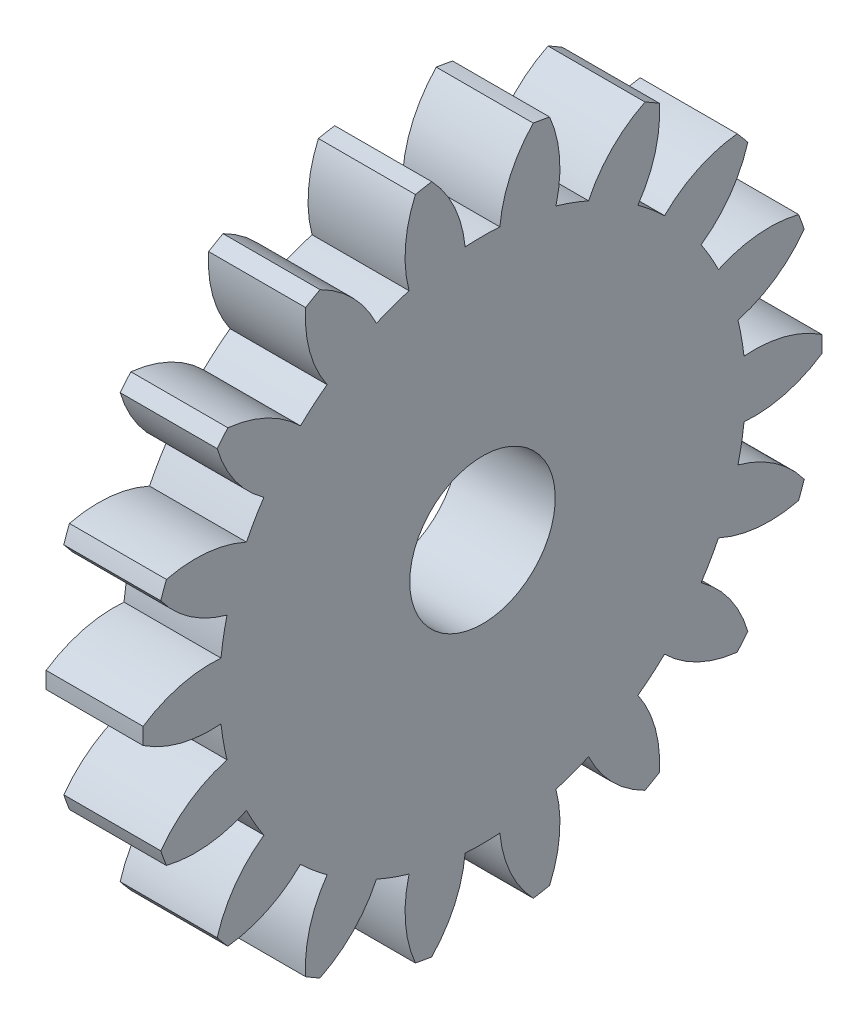
SolidWorks part; units mm, degrees
material "AISI 347 Annealed Stainless Steel (SS)"
ref_plane "Plane1" through (0, 0, 0) normal (0, 0, 1) x (1, 0, 0)
ref_plane "Plane2" through (0, 0, 0) normal (0, 1, 0) x (1, 0, 0)
ref_plane "Plane3" through (0, 0, 0) normal (1, 0, 0) x (0, 0, -1)
sketch "HoldingSke" plane through (0, 0, 0) normal (0, 1, 0) x (1, 0, 0)
  line L0 (0, 0) -> (1.3587, -0.4415)
  line L1 (-15, 0) -> (100, 0) construction
  line L2 (0, 0) -> (-2.1039, 2.3779)
  line L3 (0, 0) -> (-11.863, 4.5341)
  line L4 (0, 0) -> (8.2133, 2.6687)
  line L5 (0, 0) -> (-46.8476, -17.4728)
  line L6 (0, 0) -> (-1.6579, -1.1186)
  line L7 (-2.1039, 2.3779) -> (8.6586, 51.2059)
  line L8 (-76.2, 54.61) -> (-75.7, 54.61)
  line L9 (-71.009, 38.7566) -> (-53.1078, 45.2721)
  line L10 (-76.2, 71.12) -> (104.1128, 71.12)
  line L11 (0, 0) -> (-2, 0)
  line L12 (-76.2, 101.6) -> (-76.173, 101.6)
  line L13 (24.9733, 27.94) -> (52.9518, 28.4284)
  line L14 (24.9733, 27.94) -> (24.9743, 27.94)
  line L15 (24.9733, 27.94) -> (100.4006, 29.5858)
  line L16 (-63.627, -0.7) -> (-12.827, -0.7)
  circle A0 centre (0, 0) radius 1.5
  circle A1 centre (0, 0) radius 5.424
  circle A2 centre (0, 0) radius 37.5
  circle A3 centre (0, 0) radius 1.5
  dimension "MHD" = 10.848
  dimension "Hub_dia" = 75
  dimension "Bore" = 3
  dimension "MBD" = 3
  dimension "Num_teeth" = 18
  dimension "Pitch" = 1.4286
  dimension "Overall_len" = 50
  dimension "Show_teeth" = 18
  dimension "Thickness" = 2
  dimension "OAL" = 50.0001
  dimension "T_dim" = 0.5
  dimension "Ap" = 20
  dimension "H" = 19.05
  dimension "Pitch_radius" = 180.3128
  dimension "Width" = 2
  dimension "Backlash" = 0.027
  dimension "Addendum_fac" = 1
  dimension "Dedendum_fac" = 1.25
  dimension "Clearance_fac" = 0.25
  dimension "Dedendum_add" = 0.001
  dimension "Module" = 0.7
sketch "BasProSke" plane through (0, 0, 0) normal (0, 1, 0) x (1, 0, 0)
  line L0 (-10, 0) -> (60, 0) construction
  line L1 (0, 0) -> (0, 7)
  line L2 (0, 0) -> (2, 0)
  line L3 (2, 0) -> (2, 7)
  line L4 (2, 7) -> (0, 7)
  dimension "Thickness" = 2
  dimension "Diameter" = 14
revolve "Base-Revolve" add sketch "BasProSke" angle 360 about L0
sketch "TooCutSke" plane through (0, 0, 0) normal (1, 0, 0) x (0, 0, -1)
  line L1 (0, 0) -> (0, 107) construction
  line L2 (0, 0) -> (-0.5963, 6.2717) construction
  line L3 (0, 0) -> (-2.181, 12.3691) construction
  line L4 (-0.5963, 6.2717) -> (-1.0905, 6.1846) construction
  arc A0 (0.358, 5.4122) -> (-0.358, 5.4122) centre (0, 0) ccw
  arc A1 (1.068, 6.9438) -> (-1.068, 6.9438) centre (0, 0) ccw
  circle A2 centre (0, 0) radius 6.3 construction
  circle A3 centre (0, 0) radius 5.9201 construction
  arc A4 (-0.358, 5.4122) -> (-1.068, 6.9438) centre (-2.8672, 5.1794) ccw
  arc A5 (1.068, 6.9438) -> (0.358, 5.4122) centre (2.8672, 5.1794) ccw
  dimension "Root_dia" = 10.848
  dimension "Overcut_dia" = 14.0508
  dimension "Pitch_dia" = 12.6
  dimension "Base_dia" = 11.8401
  dimension "Flank_rad" = 2.52
  dimension "Half_ang" = 10
  dimension "Half_CT" = 0.5018
extrude "ToothCut" cut sketch "TooCutSke" along normal through all
fillet "Breaks" [suppressed] radius 0.014
fillet "RootFillets" [suppressed] radius 0.176
pattern_circular "TeethCuts" count 18 every 20 about axis through (-10, 0, 0) along (1, 0, 0) of "ToothCut", "RootFillets", "Breaks"
sketch "HubNeaOneSke" plane through (0, 0, 0) normal (-1, 0, 0) x (0, 0, 1)
  circle A0 centre (0, 0) radius 5.424
  dimension "Diameter" = 10.848
extrude "HubNearOne" [suppressed] add sketch "HubNeaOneSke" along normal blind 48.0001
sketch "HubNeaBotSke" plane through (0, 0, 0) normal (-1, 0, 0) x (0, 0, 1)
  circle A0 centre (0, 0) radius 5.424
  dimension "Diameter" = 10.848
extrude "HubNearBoth" [suppressed] add sketch "HubNeaBotSke" along normal blind 24
ref_plane "FarPln" through (2, 0, 0) normal (1, 0, 0) x (0, 0, -1)
sketch "HubFarSke" plane through (2, 0, 0) normal (1, 0, 0) x (0, 0, -1)
  circle A0 centre (0, 0) radius 5.424
  dimension "Diameter" = 10.848
extrude "HubFar" [suppressed] add sketch "HubFarSke" along normal blind 24
sketch "BorSke" plane through (0, 0, 0) normal (1, 0, 0) x (0, 0, -1)
  circle A0 centre (0, 0) radius 1.5
  dimension "Diameter" = 3
extrude "Bore" cut sketch "BorSke" along normal mid plane 100.0001
sketch "KeySke" plane through (0, 0, 0) normal (1, 0, 0) x (0, 0, -1)
  line L0 (-0.6, 0) -> (-0.6, 2)
  line L1 (-0.6, 2) -> (0.6, 2)
  line L2 (0.6, 2) -> (0.6, 0)
  line L3 (0, 0) -> (0, 34) construction
  line L4 (-0.6, 0) -> (0.6, 0)
  dimension "Offset" = 2
  dimension "Width" = 1.2
extrude "Keyway" [suppressed] cut sketch "KeySke" along normal mid plane 100.0001
pattern_circular "Keyway2" [suppressed] count 2 every 90 about axis through (-10, 0, 0) along (1, 0, 0)
equation "' \"Module@HoldingSke\" = 6.35"
equation "' \"Num_teeth@HoldingSke\" = 12"
equation "' \"Ap@HoldingSke\" =  20"
equation "' \"Ap@HoldingSke\" = 20"
equation "' \"Width@HoldingSke\" = 0.5 * 25.4"
equation "' \"Hub_dia@HoldingSke\"= 1 * 25.4"
equation "' \"Hub_dia@HoldingSke\" = 1 * 25.4"
equation "' \"Overall_len@HoldingSke\" = 1.0 * 25.4"
equation "' \"Bore@HoldingSke\" = 0.75 * 25.4"
equation "' \"T_dim@HoldingSke\" = 0.1 * 25.4"
equation "' \"Width@KeySke\" = 0.25 * 25.4"
equation "' \"Show_teeth@HoldingSke\" = 13"
equation "' \"Backlash@HoldingSke\" = 0.009 * 25.4"
equation "' \"Addendum_fac@HoldingSke\" = 1.0"
equation "' \"Dedendum_fac@HoldingSke\" = 1.25"
equation "' \"Dedendum_add@HoldingSke\" = 0.00005 * 25.4"
equation "' \"Clearance_fac@HoldingSke\" = 0.25"
equation "\"Pitch@HoldingSke\" = 1 / \"Module@HoldingSke\""
equation "\"Overcut_dia@TooCutSke\" = (\"Num_teeth@HoldingSke\" + 2 * \"Addendum_fac@HoldingSke\") / \"Pitch@HoldingSke\" + 0.002 * 25.4"
equation "\"Pitch_dia@TooCutSke\" = \"Num_teeth@HoldingSke\" / \"Pitch@HoldingSke\""
equation "\"Base_dia@TooCutSke\" = \"Num_teeth@HoldingSke\" / \"Pitch@HoldingSke\" * cos((\"Ap@HoldingSke\"  * 3.14159265 / 180))"
equation "\"Root_dia@TooCutSke\" = (\"Num_teeth@HoldingSke\" + 2) / \"Pitch@HoldingSke\" - 2 * (\"Addendum_fac@HoldingSke\" + \"Dedendum_fac@HoldingSke\") / \"Pitch@HoldingSke\" - \"Dedendum_add@HoldingSke\" * 2"
equation "\"Half_ang@TooCutSke\" = 180 / \"Num_teeth@HoldingSke\""
equation "\"Half_CT@TooCutSke\" = \"Num_teeth@HoldingSke\" / \"Pitch@HoldingSke\" * sin((3.14159265 / 2 / \"Num_teeth@HoldingSke\")) / 2 - 7 * \"Backlash@HoldingSke\" / 4"
equation "\"Flank_rad@TooCutSke\" = \"Num_teeth@HoldingSke\" / \"Pitch@HoldingSke\" / 5"
equation "\"Radius@RootFillets\" = \"Clearance_fac@HoldingSke\" / \"Pitch@HoldingSke\" + \"Dedendum_add@HoldingSke\""
equation "\"Break_rad@Breaks\" = 0.02 / \"Pitch@HoldingSke\""
equation "\"Thickness@HoldingSke\" = \"Width@HoldingSke\""
equation "\"OAL@HoldingSke\" = \"Thickness@HoldingSke\""
equation "\"MHD@HoldingSke\" = (\"Num_teeth@HoldingSke\" + 2) / \"Pitch@HoldingSke\" - 2 * (\"Addendum_fac@HoldingSke\" + \"Dedendum_fac@HoldingSke\")  / \"Pitch@HoldingSke\" - \"Dedendum_add@HoldingSke\" * 2"
equation "\"MBD@HoldingSke\" = (\"Num_teeth@HoldingSke\" + 2) / \"Pitch@HoldingSke\" - 2 * (\"Addendum_fac@HoldingSke\" + \"Dedendum_fac@HoldingSke\")  / \"Pitch@HoldingSke\" - \"Dedendum_add@HoldingSke\" * 2 - 0.002 * 25.4"
equation "\"MHD@HoldingSke\" = ((sgn( \"MHD@HoldingSke\" - \"Hub_dia@HoldingSke\" )-1)*( \"MHD@HoldingSke\" - \"Hub_dia@HoldingSke\" ))/-2+ \"Hub_dia@HoldingSke\""
equation "\"MBD@HoldingSke\" = ((sgn( \"MBD@HoldingSke\" - \"Bore@HoldingSke\" )-1)*( \"MBD@HoldingSke\" - \"Bore@HoldingSke\" ))/-2+ \"Bore@HoldingSke\""
equation "\"OAL@HoldingSke\" = ((sgn( \"OAL@HoldingSke\" - \"Overall_len@HoldingSke\" )+1)*( \"OAL@HoldingSke\" - \"Overall_len@HoldingSke\" ))/2 + \"Overall_len@HoldingSke\" + 0.000002 * 25.4"
equation "\"Num_teeth@TeethCuts\" = int( \"Show_teeth@HoldingSke\" ) + 1"
equation "\"Num_teeth@TeethCuts\" = ((sgn( \"Num_teeth@TeethCuts\" - \"Num_teeth@HoldingSke\" )-1)*( \"Num_teeth@TeethCuts\" - \"Num_teeth@HoldingSke\" ))/-2+ \"Num_teeth@HoldingSke\""
equation "\"Num_teeth@TeethCuts\" = ((sgn( \"Num_teeth@TeethCuts\" - 2.0)+1)*( \"Num_teeth@TeethCuts\" - 2.0))/2 +2.0"
equation "\"Angle@TeethCuts\" = 360.0 / \"Num_teeth@HoldingSke\""
equation "\"Diameter@BasProSke\" = (\"Num_teeth@HoldingSke\" + 2 * \"Addendum_fac@HoldingSke\") / \"Pitch@HoldingSke\""
equation "\"Thickness@BasProSke\"  = \"Thickness@HoldingSke\""
equation "' \"Fillet_rad@BasProSke\" =  \"Thickness@HoldingSke\" * 0.05"
equation "' \"Fillet_rad@BasProSke\" = \"Thickness@HoldingSke\" * 0.05"
equation "\"MHD@HoldingSke\" = ((sgn( \"MHD@HoldingSke\" - \"Root_dia@TooCutSke\" )-1)*( \"MHD@HoldingSke\" - \"Root_dia@TooCutSke\" ))/-2+ \"Root_dia@TooCutSke\""
equation "\"Diameter@HubNeaOneSke\" = \"MHD@HoldingSke\""
equation "\"Length@HubNearOne\" = \"OAL@HoldingSke\" - \"Thickness@BasProSke\""
equation "\"Diameter@HubNeaBotSke\" = \"MHD@HoldingSke\""
equation "\"Length@HubNearBoth\" = ( \"OAL@HoldingSke\" - \"Thickness@BasProSke\" ) / 2.0"
equation "\"Thickness@FarPln\" = \"Thickness@BasProSke\""
equation "\"Diameter@HubFarSke\" = \"MHD@HoldingSke\""
equation "\"Length@HubFar\" = ( \"OAL@HoldingSke\" - \"Thickness@BasProSke\" ) / 2.0"
equation "\"Diameter@BorSke\" = \"MBD@HoldingSke\""
equation "\"D1@Bore\" = \"OAL@HoldingSke\" * 2.0"
equation "\"D1@Keyway\" = \"OAL@HoldingSke\" * 2.0"
equation "\"Offset@KeySke\" = \"T_dim@HoldingSke\" + \"MBD@HoldingSke\" / 2.0"
